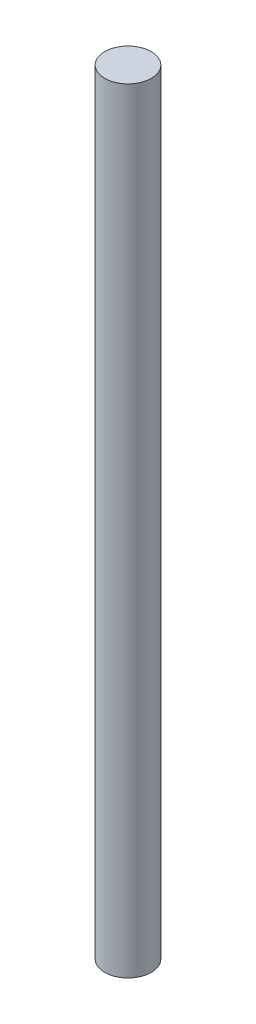
SolidWorks part; units mm, degrees
ref_plane "Front Plane" through (0, 0, 0) normal (0, 0, 1) x (1, 0, 0)
ref_plane "Top Plane" through (0, 0, 0) normal (0, 1, 0) x (1, 0, 0)
ref_plane "Right Plane" through (0, 0, 0) normal (1, 0, 0) x (0, 0, -1)
sketch "Sketch1" plane through (0, 0, 0) normal (0, 0, 1) x (1, 0, 0)
  line L0 (0, 0) -> (0, 150000) construction
  line L1 (4500, 0) -> (4500, 150000) construction
  line L2 (-4500, 0) -> (-4500, 150000) construction
sketch "Sketch2" plane through (0, 0, 0) normal (0, 1, 0) x (1, 0, 0)
  circle A0 centre (0, 0) radius 4500
extrude "Boss-Extrude1" add sketch "Sketch2" along normal blind 150000
ref_plane "Plane1" through (0, 76500, 0) normal (0, 1, 0) x (1, 0, 0)
ref_plane "Plane2" through (0, 80000, 0) normal (0, 1, 0) x (1, 0, 0)
ref_plane "Plane3" through (0, 150000, 0) normal (0, 1, 0) x (1, 0, 0)
